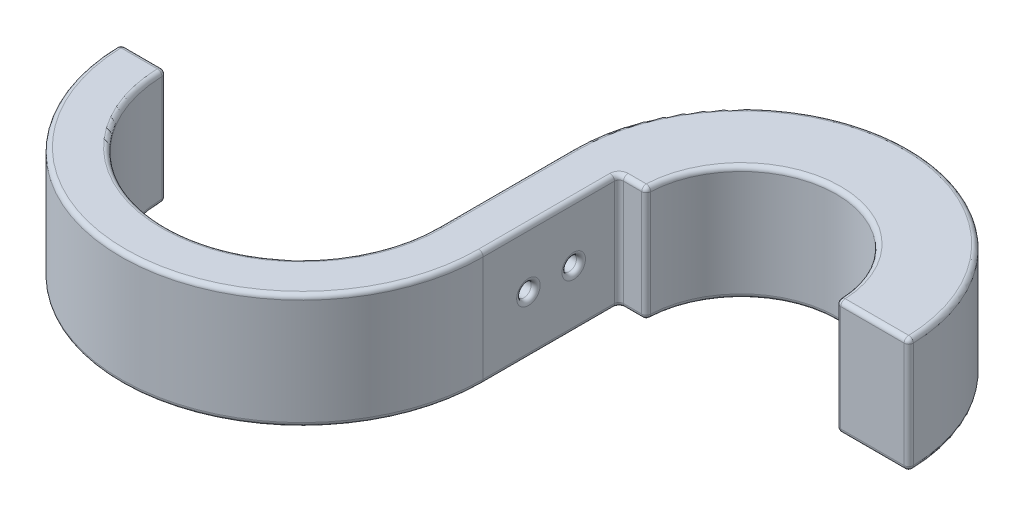
SolidWorks part; units mm, degrees
ref_plane "Front Plane" through (0, 0, 0) normal (0, 0, 1) x (1, 0, 0)
ref_plane "Top Plane" through (0, 0, 0) normal (0, 1, 0) x (1, 0, 0)
ref_plane "Right Plane" through (0, 0, 0) normal (1, 0, 0) x (0, 0, -1)
sketch "Sketch1" plane through (0, 0, 0) normal (0, 1, 0) x (1, 0, 0)
  line L0 (42, 0) -> (58, 0)
  line L1 (0, 0) -> (-6, 0)
  line L2 (-16, 0) -> (-16, -30)
  line L3 (-6, 0) -> (-6, -30)
  line L4 (-86, -30) -> (-76, -30)
  circle A0 centre (21, 0) radius 21 construction
  arc A1 (58, 0) -> (-16, 0) centre (21, 0) ccw
  circle A2 centre (-46, -30) radius 30 construction
  arc A3 (-16, -30) -> (-76, -30) centre (-46, -30) cw
  arc A4 (-6, -30) -> (-86, -30) centre (-46, -30) cw
  arc A5 (0, 0) -> (42, 0) centre (21, 0) cw
  dimension "D1" = 10
  dimension "D3" = 37
  dimension "D4" = 30
  dimension "D5" = 21
  dimension "D2" = 6
extrude "Boss-Extrude1" add sketch "Sketch1" along normal blind 25.4 contours L3 A4 L4 A3 L2 A1 L0 A5 L1
sketch "Sketch3" plane through (-6, 0, 0) normal (1, 0, 0) x (0, 0, -1)
  circle A0 centre (-20, 12.7) radius 1.6
  circle A1 centre (-10, 12.7) radius 1.6
extrude "Cut-Extrude2" cut sketch "Sketch3" against normal through all
fillet "Fillet1" radius 1 28 edges at (0, 12.7, 0) (42, 12.7, 0) (58, 12.7, 0) (-16, 12.7, 18.4) (-16, 12.7, 8.4) (-76, 12.7, 30) (-86, 12.7, 30) (-6, 12.7, 0) (-6, 12.7, 18.4) (-6, 12.7, 8.4) (-6, 25.4, 15) (-46, 25.4, 70) (-81, 25.4, 30) (-46, 25.4, 60) (-16, 25.4, 15) (21, 25.4, -37) (50, 25.4, 0) (21, 25.4, -21) (-3, 25.4, 0) (21, 0, -21) (50, 0, 0) (21, 0, -37) (-16, 0, 15) (-46, 0, 60) (-81, 0, 30) (-46, 0, 70) (-6, 0, 15) (-3, 0, 0)
